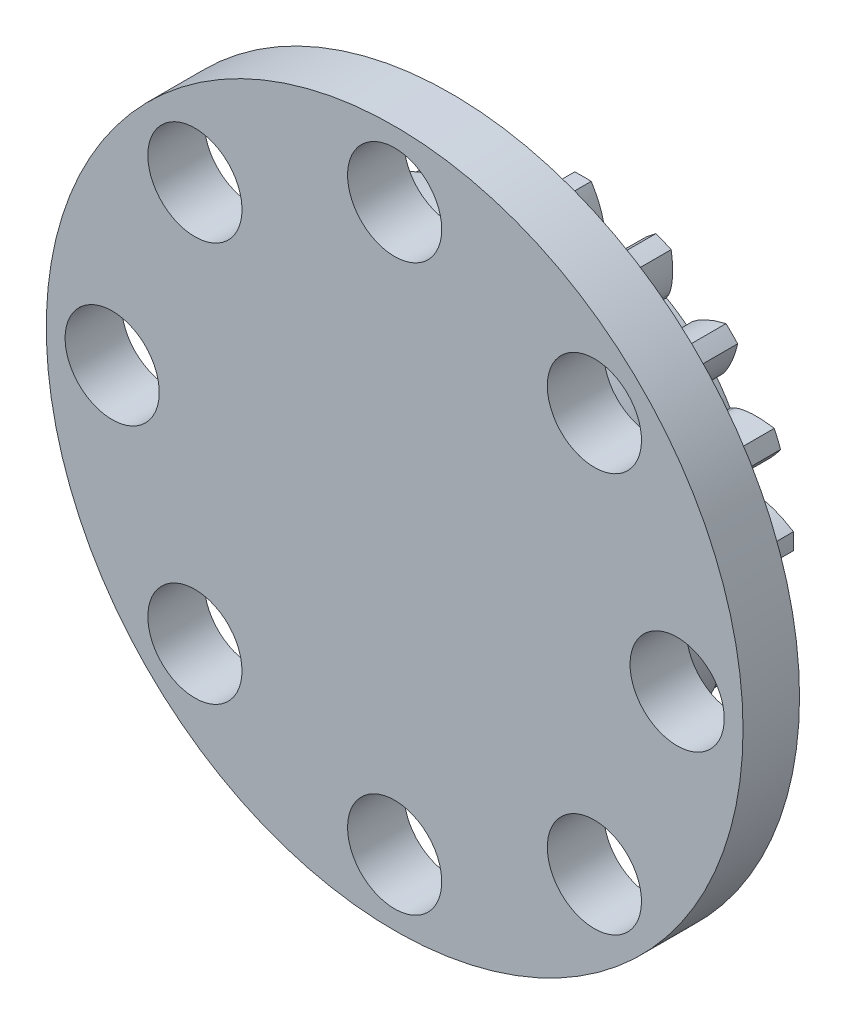
SolidWorks part; units mm, degrees
material "ABS"
ref_plane "Front Plane" through (0, 0, 0) normal (0, 0, 1) x (1, 0, 0)
ref_plane "Top Plane" through (0, 0, 0) normal (0, 1, 0) x (1, 0, 0)
ref_plane "Right Plane" through (0, 0, 0) normal (1, 0, 0) x (0, 0, -1)
sketch "Definition Drawing" plane through (0, 0, 0) normal (0, 0, 1) x (1, 0, 0)
  line L0 (11.1859, 0) -> (9.1859, 0) construction
  line L1 (0, 0) -> (-4.9116, 7.8165) construction
  line L2 (0, 0) -> (0, 11.1859) construction
  line L3 (0, 0) -> (1.1349, 9.1615) construction
  line L4 (-4.9116, 7.8165) -> (0.437, 11.1774) construction
  line L5 (0, 0) -> (0.9486, 10.1416) construction
  line L6 (0, 0) -> (0.9984, 10.1369) construction
  line L7 (0, 0) -> (-3.5093, 8.5385) construction
  line L8 (-3.5093, 8.5385) -> (0.8727, 10.3395) construction
  line L9 (0, 0) -> (-2.0045, 9.0113) construction
  line L10 (-2.0045, 9.0113) -> (1.0785, 9.6971) construction
  line L11 (0, 0) -> (-0.4412, 9.221) construction
  line L12 (-0.4412, 9.221) -> (1.1362, 9.2965) construction
  circle A0 centre (0, 0) radius 9.2316 construction
  circle A1 centre (0, 0) radius 9.1859 construction
  circle A2 centre (0, 0) radius 10.1859 construction
  circle A3 centre (0, 0) radius 11.1859 construction
  circle A4 centre (0, 0) radius 8.9859 construction
  arc A5 (0.9486, 10.1416) -> (0.9984, 10.1369) centre (0, 0) cw construction
  spline S0 degree 3 poles (1.1349, 9.1615) (1.1454, 9.3416) (1.0377, 10.0598) (0.7215, 10.7202) (0.437, 11.1774) knots 0 0 0 0 0.250023 1 1 1 1 construction
  point P13 (10.1859, 0)
  dimension "D4" = 20.3718
  dimension "D5" = 18.4632
  dimension "D1" = 2
  dimension "D2" = 0.2
  dimension "D3" = 5.625
  dimension "D6" = 0.05
  dimension "D7" = 39.206
  dimension "D11" = 4.7376
  dimension "D12" = 3.1584
  dimension "D13" = 1.5792
  dimension "D8" = 29.404
  dimension "D9" = 19.603
  dimension "D10" = 9.801
sketch "Sketch5" plane through (0, 0, 0) normal (0, 0, 1) x (1, 0, 0)
  circle A1 centre (0, 0) radius 8.9859
  circle A2 centre (0, 0) radius 1.5
  circle A3 centre (0, 0) radius 8.9859 construction
  dimension "D1" = 3
extrude "Extrude Body" add sketch "Sketch5" along normal mid plane 4
sketch "Sketch6" plane through (0, 0, 0) normal (0, 0, 1) x (1, 0, 0)
  line L0 (0, 11.1859) -> (0, 0) construction
  line L4 (1.1349, 9.1615) -> (0.1844, 1.4886)
  line L5 (0, 0) -> (1.1349, 9.1615) construction
  line L6 (-1.1349, 9.1615) -> (-0.1844, 1.4886)
  arc A0 (0.437, 11.1774) -> (-0.437, 11.1774) centre (0, 0) ccw
  arc A3 (0.1844, 1.4886) -> (-0.1844, 1.4886) centre (0, 0) ccw
  circle A4 centre (0, 0) radius 1.5 construction
  spline S0 degree 3 poles (1.1349, 9.1615) (1.1454, 9.3416) (1.0377, 10.0598) (0.7215, 10.7202) (0.437, 11.1774) knots 0 0 0 0 0.250023 1 1 1 1
  spline S1 degree 3 poles (-1.1349, 9.1615) (-1.1454, 9.3416) (-1.0377, 10.0598) (-0.7215, 10.7202) (-0.437, 11.1774) knots 0 0 0 0 0.250023 1 1 1 1
extrude "Extrude Tooth" add sketch "Sketch6" along normal mid plane 4
pattern_circular "CirPattern1" count 16 over 360 about axis through (0, 0, 2) along (0, 0, -1) of "Extrude Tooth"
sketch "Sketch8" plane through (0, 0, 0) normal (0, 0, 1) x (1, 0, 0)
  line L6 (0, 11.1859) -> (0, 0) construction
  line L7 (0, 0) -> (0, -11.1859) construction
  line L8 (1.5, 4.3139) -> (1.5, 4.899)
  line L9 (1.5, -4.899) -> (1.5, -4.3139)
  circle A2 centre (0, 0) radius 11.1859 construction
  arc A20 (3.0014, -5.1791) -> (3.0014, 5.1791) centre (0, 0) ccw
  circle A21 centre (0, 0) radius 8.9859 construction
  arc A23 (1.5, -4.3139) -> (3.0014, -5.1791) centre (2.5, -4.3139) ccw
  arc A24 (1.5, -4.899) -> (2.0455, -4.0083) centre (2.5, -4.899) cw
  arc A25 (1.5, 4.899) -> (2.0455, 4.0083) centre (2.5, 4.899) ccw
  arc A26 (1.5, 4.3139) -> (3.0014, 5.1791) centre (2.5, 4.3139) cw
  arc A27 (2.0455, -4.0083) -> (2.0455, 4.0083) centre (0, 0) ccw
  circle A28 centre (0, 0) radius 1.5 construction
  dimension "D1" = 3
  dimension "D6" = 1
  dimension "D4" = 3
  dimension "D5" = 3
  dimension "D2" = 3
  dimension "D3" = 180
extrude "Cut Spoke" [suppressed] cut sketch "Sketch8" against normal through all and the other way through all
pattern_circular "Pattern Spokes" [suppressed] count 2 over 360
ref_plane "Plane1" through (0, 0, 8) normal (0, 0, 1) x (1, 0, 0)
ref_plane "Plane2" through (5, 0, 0) normal (1, 0, 0) x (0, 0, -1)
sketch "Sketch14" plane through (0, 0, 8) normal (0, 0, 1) x (1, 0, 0)
  circle A0 centre (0, 0) radius 18.5
  dimension "D1" = 37
extrude "Boss-Extrude3" add sketch "Sketch14" against normal blind 3 separate body
sketch "Sketch15" plane through (0, 0, 5) normal (0, 0, -1) x (-1, 0, 0)
  circle A0 centre (0, 0) radius 12
  dimension "D1" = 24
extrude "Boss-Extrude4" add sketch "Sketch15" along normal up to surface (3 mm away) up to face at (0, 0, 2)
sketch "Sketch9" plane through (5, 0, 0) normal (1, 0, 0) x (0, 0, -1)
  line L0 (-8, 16.7) -> (-30.85, 16.7)
  line L1 (-8, 19.25) -> (-8, -19.25) construction
  line L2 (-30.85, 16.7) -> (-30.85, 11)
  line L3 (-30.85, 11) -> (-13, 11)
  line L4 (-13, 11) -> (-13, -11)
  line L5 (-13, 0) -> (-8, 0) construction
  line L6 (-8, -16.7) -> (-8, 16.7)
  line L7 (-30.85, -16.7) -> (-30.85, -11)
  line L8 (-8, -16.7) -> (-30.85, -16.7)
  line L9 (-30.85, -11) -> (-13, -11)
  circle A0 centre (-28, 13.85) radius 1.4
  circle A1 centre (-28, 13.85) radius 2.85 construction
  circle A2 centre (-28, -13.85) radius 1.4
  point P18 (0, 0)
  point P19 (0, 0)
  point P20 (0, 0)
  dimension "D2" = 2.8
  dimension "D1" = 13.85
  dimension "D3" = 11
  dimension "D4" = 20
  dimension "D5" = 15
sketch "Sketch16" plane through (0, 0, 5) normal (0, 0, 1) x (1, 0, 0)
  line L0 (0, 0) -> (0, 15) construction
  circle A0 centre (0, 15) radius 2.5
  dimension "D2" = 5
  dimension "D1" = 15
extrude "Cut-Extrude1" cut sketch "Sketch16" along normal through all
pattern_circular "CirPattern2" count 8 over 360 about axis through (0, 0, 0) along (0, 0, 1) of "Cut-Extrude1"
sketch "Sketch17" plane through (0, 0, -2) normal (0, 0, -1) x (-1, 0, 0)
  circle A0 centre (0, 0) radius 4
  dimension "D1" = 8
extrude "Cut-Extrude2" cut sketch "Sketch17" against normal up to surface (4 mm away) up to face at (1.5, 0, 2)
equation "\"nTeeth\"= 16"
equation "\"xThickness\"= 4"
equation "\"dShaft\"= 3"
equation "\"aPressure\"=25"
equation "\"pitch\"= 4"
equation "\"rHeight\"= 2"
equation "\"rClearance\"= 0.2"
equation "\"xClearance\"=0.05"
equation "\"rFillet\"= 1"
equation "\"nSpokes\"= int ( ( \"nTeeth\" - 1 ) / 10 ) + 1'rounds up"
equation "\"dPitch\"= \"nTeeth\" * \"pitch\" / pi"
equation "\"xWall\"= IIF ( \"nTeeth\" > 30 , \"nTeeth\" / 10 , 3 )"
equation "\"dBase\"= \"dPitch\" * cos ( \"aPressure\" )"
equation "\"rOuter\"= \"dPitch\" / 2 + \"rHeight\" / 2"
equation "\"xInvolute\"= sqr ( \"rOuter\" ^ 2 - ( \"dBase\" / 2 ) ^ 2 )"
equation "\"aInvolute\"= 360 * \"xInvolute\" / ( \"dBase\" / 2 ) / 2 / pi"
equation "\"D1@Definition Drawing\" = \"rHeight\""
equation "\"D2@Definition Drawing\" = \"rClearance\""
equation "\"D4@Definition Drawing\" = \"dPitch\""
equation "\"D6@Definition Drawing\" = \"xClearance\""
equation "\"D5@Definition Drawing\" = \"dBase\""
equation "\"D7@Definition Drawing\" = \"aInvolute\""
equation "\"D11@Definition Drawing\" = \"xInvolute\" * 0.75"
equation "\"D12@Definition Drawing\" = \"xInvolute\" * 0.5"
equation "\"D13@Definition Drawing\" = \"xInvolute\" * 0.25"
equation "\"D8@Definition Drawing\" = \"aInvolute\" * 0.75"
equation "\"D9@Definition Drawing\" = \"aInvolute\" * 0.5"
equation "\"D10@Definition Drawing\" = \"aInvolute\" * 0.25"
equation "\"D1@Extrude Body\"=\"xThickness\""
equation "\"D1@Sketch5\"=\"dShaft\""
equation "\"D3@Definition Drawing\" = 360 / \"nTeeth\" / 2 / 2"
equation "\"D5@Sketch8\"=\"xWall\""
equation "\"D1@Sketch8\"=\"xWall\""
equation "\"D4@Sketch8\"=\"xWall\""
equation "\"D6@Sketch8\"=\"rFillet\""
equation "\"D1@Pattern Spokes\" = \"nSpokes\""
equation "\"rHub\"= IIF ( \"xWall\" * \"nSpokes\" / 6 > \"xWall\" , \"xWall\" * \"nSpokes\" / 6 , \"xWall\" )"
equation "\"D2@Sketch8\"=\"rHub\""
equation "\"D3@Sketch8\"=360/\"nSpokes\""
equation "\"D1@Extrude Tooth\" = \"xThickness\""
equation "\"D1@CirPattern1\"=\"nTeeth\""
